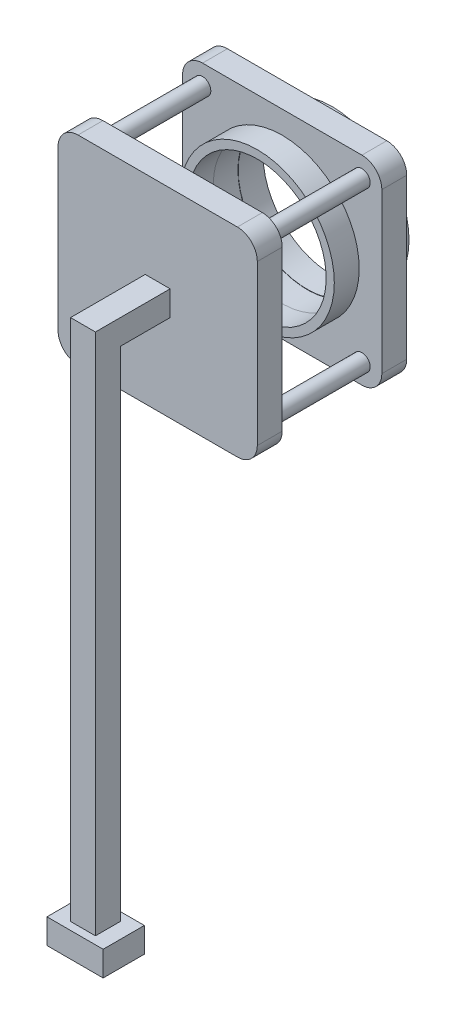
SolidWorks part; units mm, degrees
ref_plane "Front Plane" through (0, 0, 0) normal (0, 0, 1) x (1, 0, 0)
ref_plane "Top Plane" through (0, 0, 0) normal (0, 1, 0) x (1, 0, 0)
ref_plane "Right Plane" through (0, 0, 0) normal (1, 0, 0) x (0, 0, -1)
sketch "Sketch1" plane through (0, 0, 0) normal (0, 0, 1) x (1, 0, 0)
  line L1 (0, 0) -> (40, 0)
  line L2 (0, 0) -> (0, -40)
  line L3 (0, -40) -> (40, -40)
  line L4 (40, 0) -> (40, -40)
  dimension "D1" = 40
  dimension "D2" = 40
extrude "Boss-Extrude1" add sketch "Sketch1" along normal blind 5
sketch "Sketch3" plane through (0, 0, 0) normal (0, 0, -1) x (-1, 0, 0)
  line L0 (-40, 0) -> (0, 0) construction
  line L1 (-40, -40) -> (-40, 0) construction
  circle A0 centre (-20, -20) radius 13.891
  dimension "D1" = 27.782
  dimension "D2" = 20
  dimension "D3" = 20
extrude "Cut-Extrude1" cut sketch "Sketch3" against normal through all contours A0
sketch "Sketch4" plane through (0, 0, 5) normal (0, 0, 1) x (1, 0, 0)
  line L0 (0, 0) -> (0, -40) construction
  line L1 (40, 0) -> (0, 0) construction
  circle A0 centre (4, -4) radius 1.664
  circle A1 centre (36, -4) radius 1.664
  circle A2 centre (36, -36) radius 1.664
  circle A3 centre (4, -36) radius 1.664
  point P15 (20, -20)
  dimension "D1" = 4
  dimension "D2" = 4
  dimension "D3" = 4
extrude "Boss-Extrude3" add sketch "Sketch4" along normal blind 20
ref_plane "Plane1" through (0, 0, 15) normal (0, 0, 1) x (1, 0, 0)
mirror "Mirror1" about plane through (0, 0, 15) normal (0, 0, 1) of "Boss-Extrude1"
sketch "Sketch5" plane through (0, 0, 30) normal (0, 0, 1) x (1, 0, 0)
  line L1 (17.5, -17.5) -> (22.5, -17.5)
  line L2 (17.5, -17.5) -> (17.5, -22.5)
  line L3 (17.5, -22.5) -> (22.5, -22.5)
  line L4 (22.5, -17.5) -> (22.5, -22.5)
  line L5 (17.5, -17.5) -> (22.5, -22.5) construction
  line L6 (17.5, -22.5) -> (22.5, -17.5) construction
  line L7 (40, -40) -> (40, 0) construction
  line L8 (40, 0) -> (0, 0) construction
  point P0 (20, -20)
  dimension "D1" = 20
  dimension "D2" = 20
  dimension "D3" = 5
  dimension "D4" = 5
extrude "Boss-Extrude4" add sketch "Sketch5" along normal blind 15
sketch "Sketch6" plane through (0, -22.5, 0) normal (0, -1, 0) x (1, 0, 0)
  line L0 (22.5, 45) -> (22.5, 30) construction
  line L1 (17.5, 45) -> (22.5, 45)
  line L2 (17.5, 45) -> (17.5, 40)
  line L3 (17.5, 40) -> (22.5, 40)
  line L4 (22.5, 45) -> (22.5, 40)
  dimension "D1" = 5
  dimension "D2" = 5
extrude "Boss-Extrude5" add sketch "Sketch6" along normal blind 100 contours L2 L1 L4 L3
sketch "Sketch7" plane through (0, 0, 0) normal (0, 0, -1) x (-1, 0, 0)
  circle A0 centre (-20, -20) radius 13.8282
  circle A1 centre (-20, -20) radius 15.461
extrude "Boss-Extrude6" add sketch "Sketch7" along normal blind 5
ref_plane "Plane2" through (0, 0, 2.5) normal (0, 0, 1) x (1, 0, 0)
mirror "Mirror3" about plane through (0, 0, 2.5) normal (0, 0, 1) of "Boss-Extrude6"
sketch "Sketch8" plane through (0, -122.5, 0) normal (0, -1, 0) x (1, 0, 0)
  line L1 (14.3279, 46.5567) -> (25.6052, 46.5567)
  line L2 (14.3279, 46.5567) -> (14.3279, 38.2825)
  line L3 (14.3279, 38.2825) -> (25.6052, 38.2825)
  line L4 (25.6052, 46.5567) -> (25.6052, 38.2825)
extrude "Boss-Extrude7" add sketch "Sketch8" along normal blind 5
fillet "Fillet1" radius 4 1 edges at (0, 0, 2.5)
fillet "Fillet2" radius 4 7 edges at (0, -40, 27.5) (40, -40, 27.5) (0, 0, 27.5) (40, 0, 27.5) (40, -40, 2.5) (0, -40, 2.5) (40, 0, 2.5)
